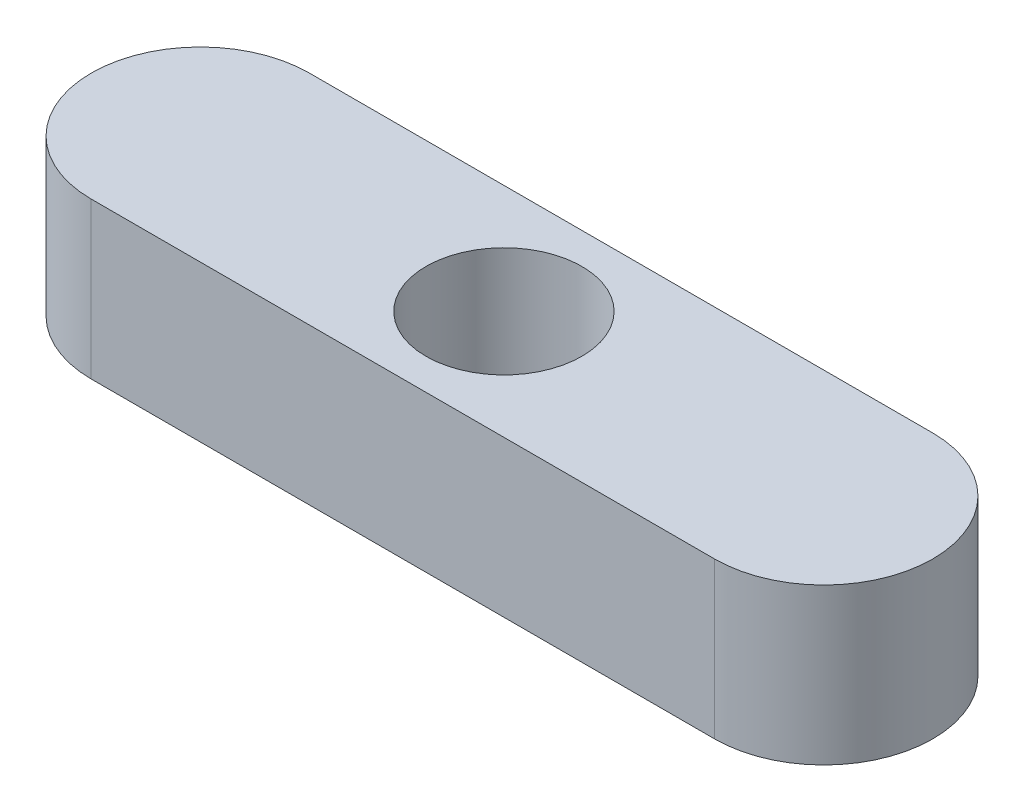
SolidWorks part; units mm, degrees
ref_plane "Front Plane" through (0, 0, 0) normal (0, 0, 1) x (1, 0, 0)
ref_plane "Top Plane" through (0, 0, 0) normal (0, 1, 0) x (1, 0, 0)
ref_plane "Right Plane" through (0, 0, 0) normal (1, 0, 0) x (0, 0, -1)
sketch "Sketch1" plane through (0, 0, 0) normal (0, 1, 0) x (1, 0, 0)
  line L1 (-12.3713, 5.5506) -> (13.0287, 5.5506)
  line L3 (-12.3713, -3.3394) -> (13.0287, -3.3394)
  arc A2 (-12.3713, 5.5506) -> (-12.3713, -3.3394) centre (-12.3713, 1.1056) ccw
  arc A3 (13.0287, 5.5506) -> (13.0287, -3.3394) centre (13.0287, 1.1056) cw
  dimension "D2" = 4.445
  dimension "D1" = 25.4
extrude "Boss-Extrude1" add sketch "Sketch1" along normal blind 6.35
sketch "Sketch2" plane through (0, 6.35, 0) normal (0, 1, 0) x (1, 0, 0)
  circle A0 centre (0, 1.1056) radius 3.175
  dimension "D1" = 6.35
extrude "Cut-Extrude1" cut sketch "Sketch2" against normal blind 6.35
sketch "Sketch19" plane through (0, 6.35, 0) normal (0, 1, 0) x (1, 0, 0)
  line L0 (-12.3713, 5.5506) -> (-12.3713, -3.3394) construction
  line L1 (13.0287, -3.3394) -> (13.0287, 5.5506) construction
sketch "Sketch21" plane through (0, 6.35, 0) normal (0, 1, 0) x (1, 0, 0)
  line L0 (-16.8163, 1.1056) -> (17.4737, 1.1056) construction
  arc A0 (-12.3713, 5.5506) -> (-12.3713, -3.3394) centre (-12.3713, 1.1056) ccw construction
  arc A1 (13.0287, -3.3394) -> (13.0287, 5.5506) centre (13.0287, 1.1056) ccw construction
